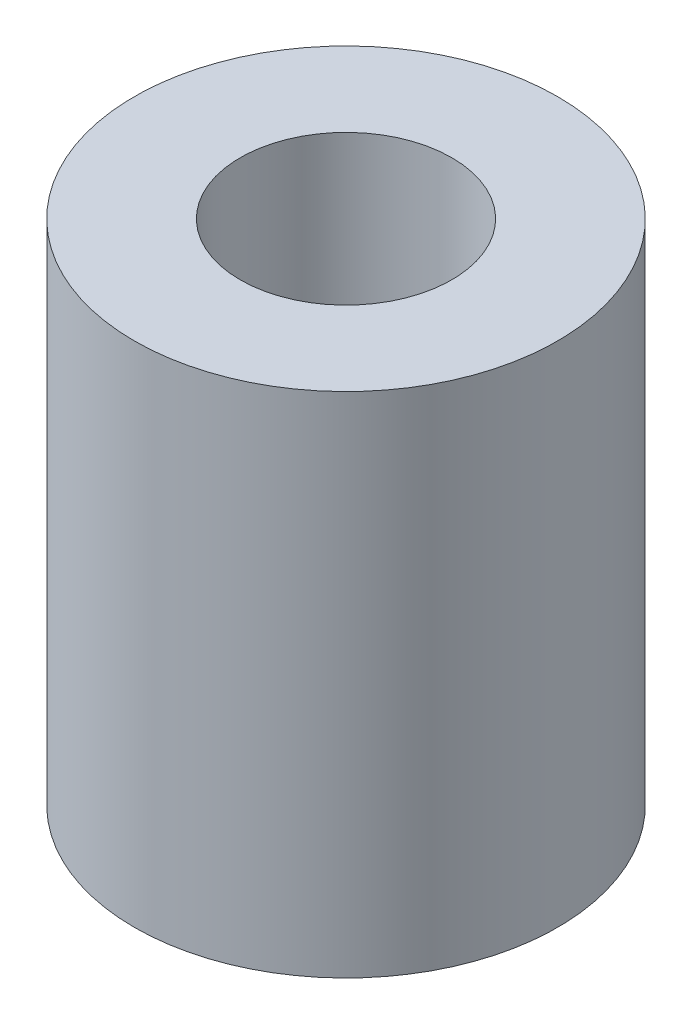
SolidWorks part; units mm, degrees
ref_plane "Front Plane" through (0, 0, 0) normal (0, 0, 1) x (1, 0, 0)
ref_plane "Top Plane" through (0, 0, 0) normal (0, 1, 0) x (1, 0, 0)
ref_plane "Right Plane" through (0, 0, 0) normal (1, 0, 0) x (0, 0, -1)
sketch "Sketch1" plane through (0, 0, 0) normal (0, 1, 0) x (1, 0, 0)
  circle A0 centre (0, 0) radius 2.5
  dimension "D1" = 5
extrude "Boss-Extrude1" add sketch "Sketch1" along normal blind 6
hole_wizard "Ø2.5mm Dowel Hole1" positions "3DSketch1" profile "Sketch2" hole size "Ø2.5" standard "DIN" end condition through all
sketch3d "3DSketch1"
  line L0 (0, 6, 0) -> (0, 0, 0) construction
  point P0 (0, 6, 0)
sketch "Sketch2" plane through (0, 6, 0) normal (1, 0, 0) x (0, 0, 1)
  line L0 (0, 0) -> (0, 6)
  line L1 (0, 6) -> (1.25, 6)
  line L2 (1.25, 6) -> (1.25, 0)
  line L5 (1.25, 0) -> (0, 0)
  line L11 (0, -6.35) -> (0, 107.95) construction
  dimension "Thru Hole Dia." = 2.5
  dimension "Thru Hole Depth" = 6
